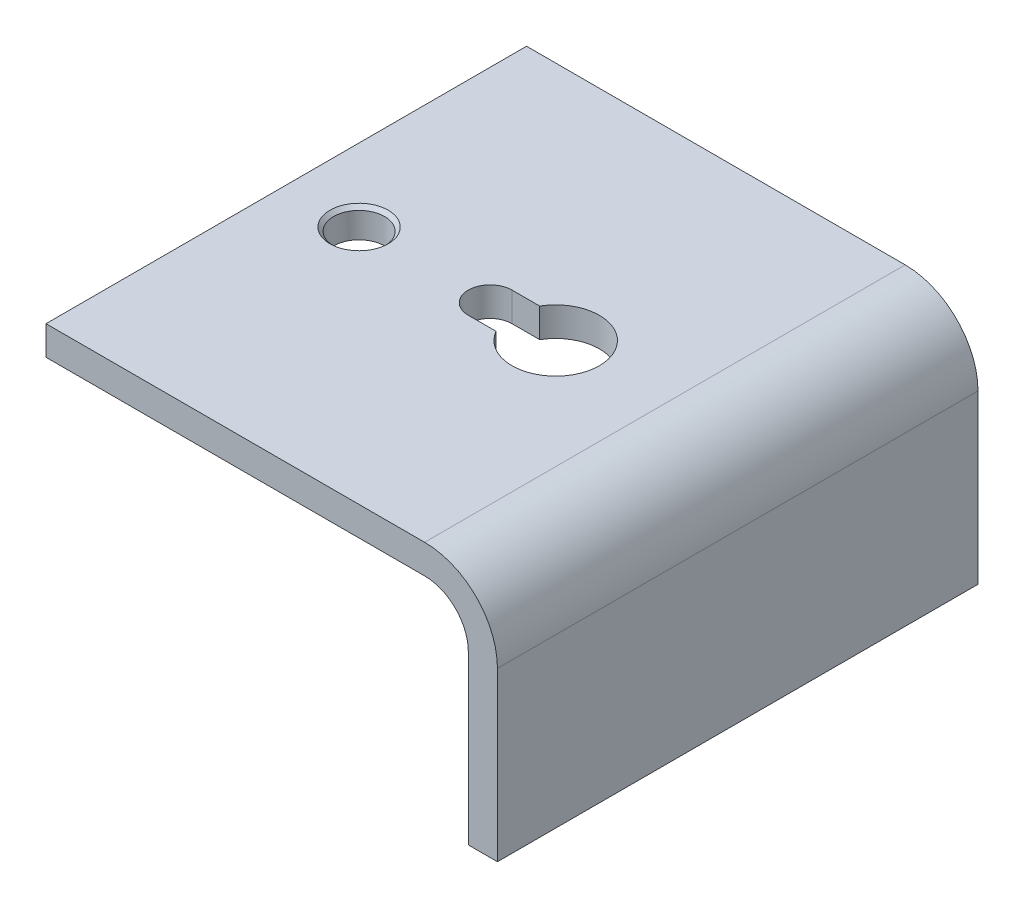
SolidWorks part; units mm, degrees
ref_plane "Front Plane" through (0, 0, 0) normal (0, 0, 1) x (1, 0, 0)
ref_plane "Top Plane" through (0, 0, 0) normal (0, 1, 0) x (1, 0, 0)
ref_plane "Right Plane" through (0, 0, 0) normal (1, 0, 0) x (0, 0, -1)
sketch "Sketch1" plane through (0, 0, 0) normal (0, 0, 1) x (1, 0, 0)
  line L0 (0, 29) -> (52, 29)
  line L3 (0, 33) -> (52, 33)
  line L4 (62, 0) -> (62, 23)
  line L5 (58, 0) -> (58, 23)
  line L6 (62, 0) -> (58, 0)
  line L7 (0, 33) -> (0, 29)
  arc A0 (52, 33) -> (62, 23) centre (52, 23) cw
  arc A1 (52, 29) -> (58, 23) centre (52, 23) cw
  point P6 (62, 33)
  dimension "D3" = 10
  dimension "D1" = 33
  dimension "D2" = 62
  dimension "D4" = 4
extrude "Boss-Extrude1" add sketch "Sketch1" along normal blind 66
sketch "Sketch2" plane through (0, 33, 0) normal (0, 1, 0) x (1, 0, 0)
  line L0 (0, -33) -> (52, -33) construction
  line L1 (0, -66) -> (0, 0) construction
  line L2 (52, -66) -> (52, 0) construction
  line L3 (37, 4.135) -> (37, -68.485) construction
  line L4 (31, -33) -> (28, -33) construction
  line L5 (28, -30) -> (31.8038, -30)
  line L6 (28, -36) -> (31.8038, -36)
  arc A0 (31.8038, -36) -> (31.8038, -30) centre (37, -33) ccw
  arc A1 (28, -30) -> (28, -36) centre (28, -33) ccw
  dimension "D1" = 15
extrude "Cut-Extrude2" cut sketch "Sketch2" against normal blind 10
sketch "Sketch3" plane through (0, 33, 0) normal (0, 1, 0) x (1, 0, 0)
  line L0 (0, -33) -> (52, -33) construction
  line L1 (0, -66) -> (0, 0) construction
  line L2 (52, -66) -> (52, 0) construction
  line L3 (10, 2.0283) -> (10, -67.6262) construction
  circle A0 centre (10, -33) radius 3.5
  dimension "D1" = 10
extrude "Cut-Extrude3" cut sketch "Sketch3" against normal blind 10
chamfer "Chamfer1" distance 0.5 angle 45 1 edges at (10, 33, 36.5)
